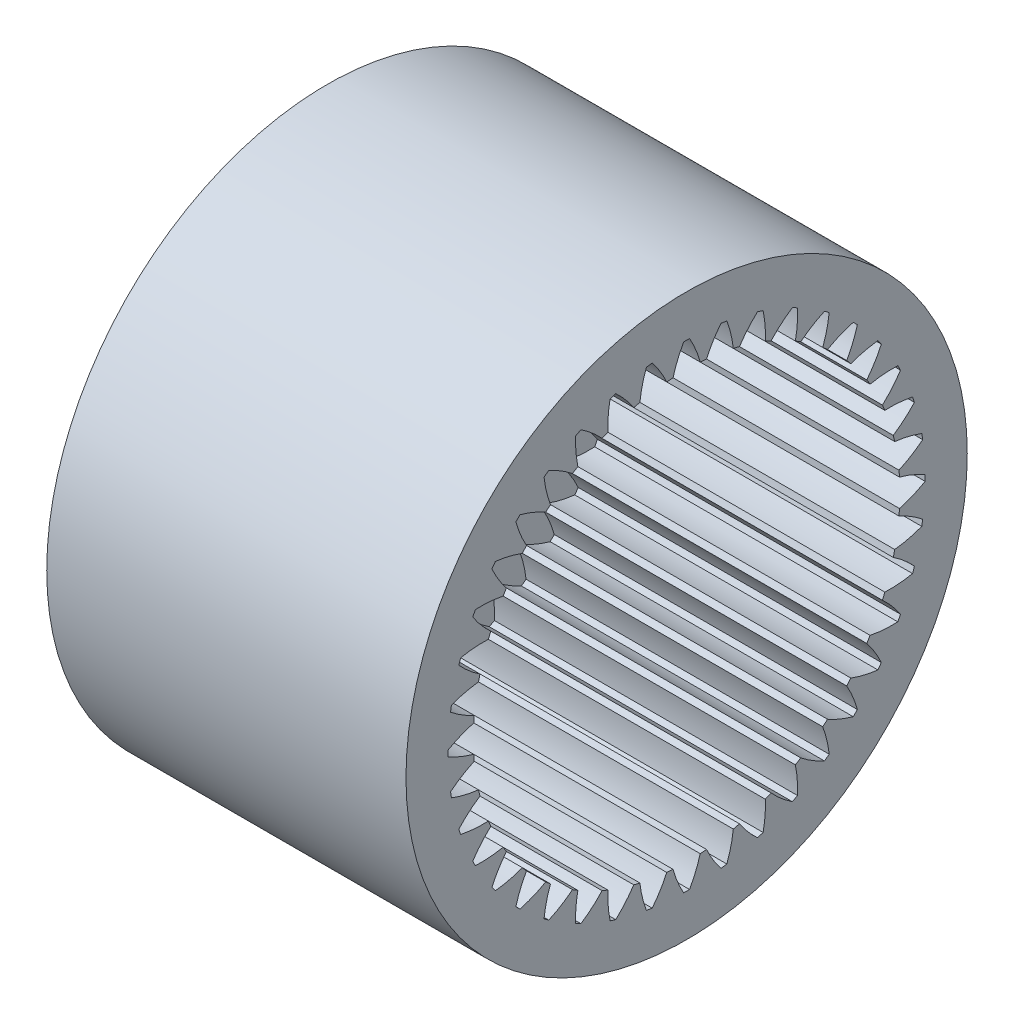
SolidWorks part; units mm, degrees
ref_plane "Plane1" through (0, 0, 0) normal (0, 0, 1) x (1, 0, 0)
ref_plane "Plane2" through (0, 0, 0) normal (0, 1, 0) x (1, 0, 0)
ref_plane "Plane3" through (0, 0, 0) normal (1, 0, 0) x (0, 0, -1)
other "Configuration Table"
sketch "HoldingSke" plane through (0, 0, 0) normal (0, 1, 0) x (1, 0, 0)
  line L0 (0, 0) -> (0.383, -0.3214)
  line L1 (-15, 0) -> (100, 0) construction
  line L2 (0, 0) -> (-2.1039, 2.3779)
  line L3 (0, 0) -> (-11.863, 4.5341)
  line L4 (0, 0) -> (6.6156, 5.5511)
  line L5 (0, 0) -> (-23.7986, -8.8762)
  line L6 (0, 0) -> (-10.5278, -7.1032)
  line L7 (-2.1039, 2.3779) -> (3.3635, 27.1825)
  line L8 (-76.2, 4.3779) -> (-54.61, 4.3779)
  line L9 (-71.009, 38.7566) -> (-53.1078, 45.2721)
  line L10 (-76.2, 71.12) -> (104.1128, 71.12)
  line L11 (0, 0) -> (-54, 0)
  line L12 (-76.2, 101.6) -> (-76.133, 101.6)
  line L13 (24.9733, 27.94) -> (52.9518, 28.4284)
  line L14 (24.9733, 27.94) -> (24.9743, 27.94)
  line L15 (24.9733, 27.94) -> (100.4006, 29.5858)
  circle A0 centre (0, 0) radius 50
  circle A1 centre (0, 0) radius 12.7
  circle A2 centre (0, 0) radius 12.7
  dimension "MHD" = 25.4
  dimension "Hub_dia" = 25.4
  dimension "Diameter" = 100
  dimension "Num_teeth" = 40
  dimension "Pitch" = 0.5
  dimension "Overall_len" = 25.4
  dimension "Show_teeth" = 40
  dimension "Thickness" = 12.7
  dimension "OAL" = 25.4001
  dimension "T_dim" = 21.59
  dimension "Ap" = 20
  dimension "H" = 19.05
  dimension "Pitch_radius" = 180.3128
  dimension "Width" = 54
  dimension "Backlash" = 0.067
  dimension "Addendum_fac" = 1
  dimension "Dedendum_fac" = 1.25
  dimension "Clearance_fac" = 0.25
  dimension "Dedendum_add" = 0.001
  dimension "Module" = 2
sketch "BasProSke" plane through (0, 0, 0) normal (0, 1, 0) x (1, 0, 0)
  line L0 (-10, 0) -> (60, 0) construction
  line L1 (0, 38) -> (0, 50)
  line L2 (0, 38) -> (54, 38)
  line L3 (54, 38) -> (54, 50)
  line L4 (54, 50) -> (0, 50)
  dimension "Diameter" = 100
  dimension "Thickness" = 54
  dimension "Inside_diameter" = 76
revolve "Base-Revolve" add sketch "BasProSke" angle 360 about L0
sketch "TooCutSke" plane through (0, 0, 0) normal (1, 0, 0) x (0, 0, -1)
  line L3 (1.7379, 39.9622) -> (1.7379, 53.6633) construction
  line L4 (0, 0) -> (0, 59.563) construction
  line L5 (0, 0) -> (-5.3609, 68.1169) construction
  line L6 (-16.8604, 32.6066) -> (35.072, 36.6938) construction
  circle A0 centre (0, 0) radius 40 construction
  circle A1 centre (0, 0) radius 42.501 construction
  circle A2 centre (0, 0) radius 33.8289 construction
  circle A3 centre (0, 0) radius 37.9746 construction
  arc A4 (2.4273, 37.8969) -> (0.5225, 42.4978) centre (-16.8604, 32.6066) ccw
  arc A5 (2.4273, 37.8969) -> (-2.4273, 37.8969) centre (0, 0) ccw
  arc A6 (0.5225, 42.4978) -> (-0.5225, 42.4978) centre (0, 0) ccw
  arc A7 (-0.5225, 42.4978) -> (-2.4273, 37.8969) centre (16.8604, 32.6066) ccw
  dimension "Pitch_dia" = 80
  dimension "Base_dia" = 67.6579
  dimension "Root_dia" = 85.002
  dimension "Overcut_dia" = 75.9492
  dimension "Flank_rad" = 20
  dimension "Half_ang" = 4.5
  dimension "Half_CT" = 1.7379
extrude "ToothCut" cut sketch "TooCutSke" along normal through all
fillet "Breaks" [suppressed] radius 0.2
fillet "RootFillets" [suppressed] radius 0.501
pattern_circular "TeethCuts" count 40 every 9 about axis through (-10, 0, 0) along (1, 0, 0) of "RootFillets", "Breaks", "ToothCut"
sketch "Sketch1" plane through (54, 0, 0) normal (1, 0, 0) x (0, 0, -1)
  circle A0 centre (0, 0) radius 11
  circle A1 centre (0, 0) radius 50
  circle A2 centre (0, 0) radius 50
  dimension "D2" = 22
  dimension "D1" = 0
sketch "Sketch2" plane through (0, 0, 0) normal (-1, 0, 0) x (0, 0, 1)
  circle A1 centre (0, 0) radius 50
  circle A2 centre (0, 0) radius 50
  circle A3 centre (0, 0) radius 11
  circle A4 centre (0, 0) radius 11
  dimension "D1" = 0
  dimension "D2" = 0
extrude "Boss-Extrude2" add sketch "Sketch2" along normal blind 10
equation "' \"Module@HoldingSke\" = 6.35"
equation "' \"Num_teeth@HoldingSke\" = 24"
equation "' \"Ap@HoldingSke\" =  14.5"
equation "' \"Ap@HoldingSke\" = 14.5"
equation "' \"Width@HoldingSke\" = 12"
equation "' \"Diameter@HoldingSke\" = 8 * 25.4"
equation "' \"Show_teeth@HoldingSke\" = 100"
equation "' \"Backlash@HoldingSke\" = 0.009 * 25.4"
equation "' \"Addendum_fac@HoldingSke\" = 1.0"
equation "' \"Dedendum_fac@HoldingSke\" = 1.25"
equation "' \"Dedendum_add@HoldingSke\" = 0.00005 * 25.4"
equation "' \"Clearance_fac@HoldingSke\" = 0.25"
equation "\"Pitch@HoldingSke\" = 1 / \"Module@HoldingSke\" "
equation "\"Overcut_dia@TooCutSke\" = (\"Num_teeth@HoldingSke\" - 2 * \"Addendum_fac@HoldingSke\") / \"Pitch@HoldingSke\" - 0.002 * 25.4"
equation "\"Pitch_dia@TooCutSke\" = \"Num_teeth@HoldingSke\" / \"Pitch@HoldingSke\""
equation "\"Base_dia@TooCutSke\" = \"Num_teeth@HoldingSke\" / \"Pitch@HoldingSke\" * cos((\"Ap@HoldingSke\"  * 3.14159265 / 180)) * 0.90"
equation "\"Root_dia@TooCutSke\" = \"Num_teeth@HoldingSke\"  / \"Pitch@HoldingSke\" + 2 *  \"Dedendum_fac@HoldingSke\"/ \"Pitch@HoldingSke\" + \"Dedendum_add@HoldingSke\" * 2"
equation "\"Half_ang@TooCutSke\" = 180 / \"Num_teeth@HoldingSke\""
equation "\"Half_CT@TooCutSke\" = \"Num_teeth@HoldingSke\" / \"Pitch@HoldingSke\" * sin((3.14159265 / 2 / \"Num_teeth@HoldingSke\")) / 2 + 10 * \"Backlash@HoldingSke\" / 4"
equation "\"Flank_rad@TooCutSke\" = \"Num_teeth@HoldingSke\" / \"Pitch@HoldingSke\" / 4"
equation "\"Radius@RootFillets\"= \"Clearance_fac@HoldingSke\" / \"Pitch@HoldingSke\" + \"Dedendum_add@HoldingSke\""
equation "\"Break_rad@Breaks\" = 0.02 / \"Pitch@HoldingSke\" * 5"
equation "\"Num_teeth@TeethCuts\" = int( \"Show_teeth@HoldingSke\" ) + 1"
equation "\"Num_teeth@TeethCuts\" = ((sgn( \"Num_teeth@TeethCuts\" - \"Num_teeth@HoldingSke\" )-1)*( \"Num_teeth@TeethCuts\" - \"Num_teeth@HoldingSke\" ))/-2+ \"Num_teeth@HoldingSke\""
equation "\"Num_teeth@TeethCuts\" = ((sgn( \"Num_teeth@TeethCuts\" - 2.0)+1)*( \"Num_teeth@TeethCuts\" - 2.0))/2 +2.0"
equation "\"Angle@TeethCuts\" = 360.0 / \"Num_teeth@HoldingSke\""
equation "\"Diameter@BasProSke\" = \"Num_teeth@HoldingSke\"  / \"Pitch@HoldingSke\" + 2 *  \"Dedendum_fac@HoldingSke\"/ \"Pitch@HoldingSke\" + \"Dedendum_add@HoldingSke\" * 2 + 0.002 * 25.4"
equation "\"Diameter@BasProSke\" = ((sgn( \"Diameter@BasProSke\"  - \"Diameter@HoldingSke\" )+1)*( \"Diameter@BasProSke\"  - \"Diameter@HoldingSke\" ))/2 + \"Diameter@HoldingSke\""
equation "\"Inside_diameter@BasProSke\" =  (\"Num_teeth@HoldingSke\" - 2 * \"Addendum_fac@HoldingSke\") / \"Pitch@HoldingSke\" "
equation "\"Thickness@BasProSke\"  = \"Width@HoldingSke\""
